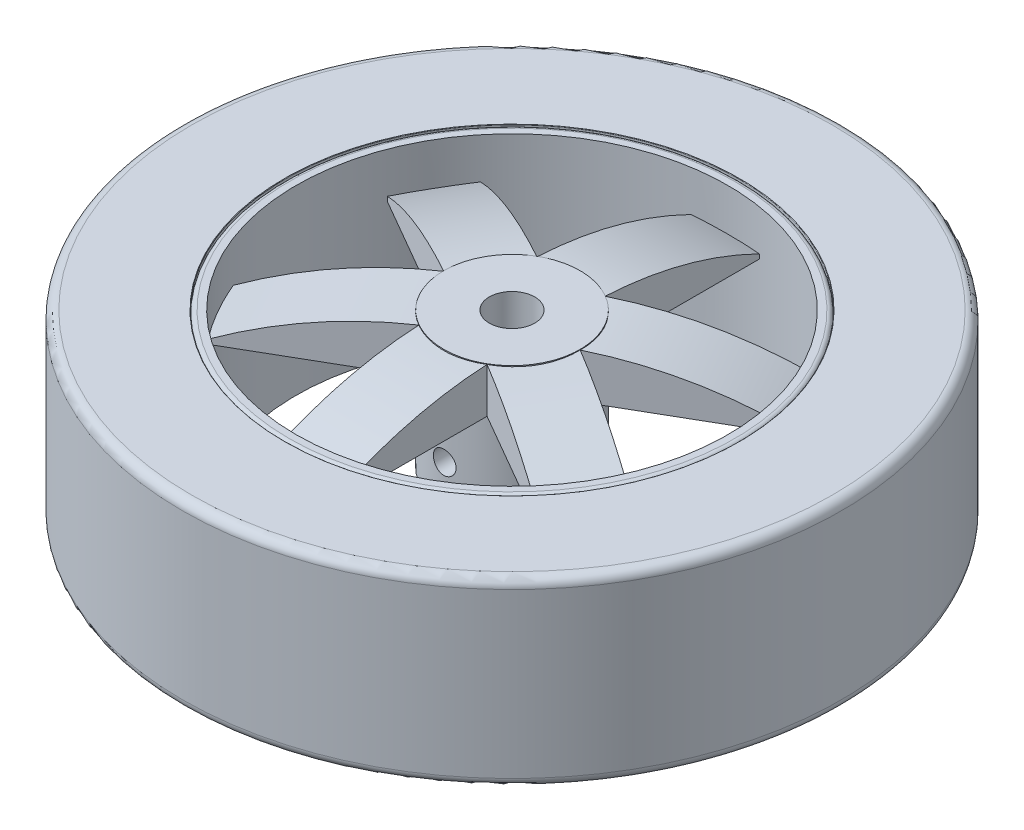
SolidWorks part; units mm, degrees
ref_plane "Front Plane" through (0, 0, 0) normal (0, 0, 1) x (1, 0, 0)
ref_plane "Top Plane" through (0, 0, 0) normal (0, 1, 0) x (1, 0, 0)
ref_plane "Right Plane" through (0, 0, 0) normal (1, 0, 0) x (0, 0, -1)
sketch "Sketch1" plane through (0, 0, 0) normal (0, 1, 0) x (1, 0, 0)
  circle A0 centre (0, 0) radius 50
  circle A1 centre (0, 0) radius 15
  circle A2 centre (0, 0) radius 47.5
  circle A3 centre (0, 0) radius 5
  dimension "D1" = 100
  dimension "D2" = 30
  dimension "D3" = 95
  dimension "D4" = 10
extrude "Boss-Extrude1" add sketch "Sketch1" along normal blind 40 contours A0 A2 | A1
ref_plane "Plane1" through (0, 20, 0) normal (0, 1, 0) x (1, 0, 0)
sketch "Sketch2" plane through (0, 0, 0) normal (1, 0, 0) x (0, 0, -1)
  line L2 (50, 40) -> (-50, 40) construction
  line L3 (48.8892, 30) -> (8.8892, 30)
  line L4 (8.8892, 30) -> (8.8892, 40)
  spline S0 degree 2 poles (8.8892, 40) (29.8688, 39.8769) (48.8892, 30) knots 0 0 0 1 1 1
  dimension "D1" = 10
  dimension "D2" = 40
  dimension "D5" = 10
extrude "Boss-Extrude2" add sketch "Sketch2" along normal mid plane 15
pattern_circular "CirPattern1" count 6 over 360 about axis through (0, 40, 0) along (0, 1, 0) of "Boss-Extrude2"
fillet "Fillet1" radius 1 2 edges at (0, 0, 50) (0, 40, 50)
sketch "Sketch5" plane through (0, 0, 0) normal (0, 1, 0) x (1, 0, 0)
  circle A0 centre (0, 0) radius 72.5
  circle A1 centre (0, 0) radius 50
  dimension "D1" = 145
  dimension "D2" = 100
extrude "Boss-Extrude4" add sketch "Sketch5" along normal blind 40
fillet "Fillet2" radius 2 2 edges at (0, 0, 72.5) (0, 40, 72.5)
fillet "Fillet3" radius 0.1 1 edges at (0, 40, 50)
sketch "Sketch7" plane through (0, 0, 0) normal (0, -1, 0) x (1, 0, 0)
  circle A1 centre (0, 0) radius 15 construction
  circle A2 centre (0, 0) radius 15
extrude "Cut-Extrude1" cut sketch "Sketch7" against normal blind 10
sketch "Sketch8" plane through (0, 0, 0) normal (0, 0, 1) x (1, 0, 0)
  circle A0 centre (0, 18.5) radius 2.5
  dimension "D1" = 5
  dimension "D2" = 8.5
extrude "Cut-Extrude2" cut sketch "Sketch8" against normal mid plane 35
